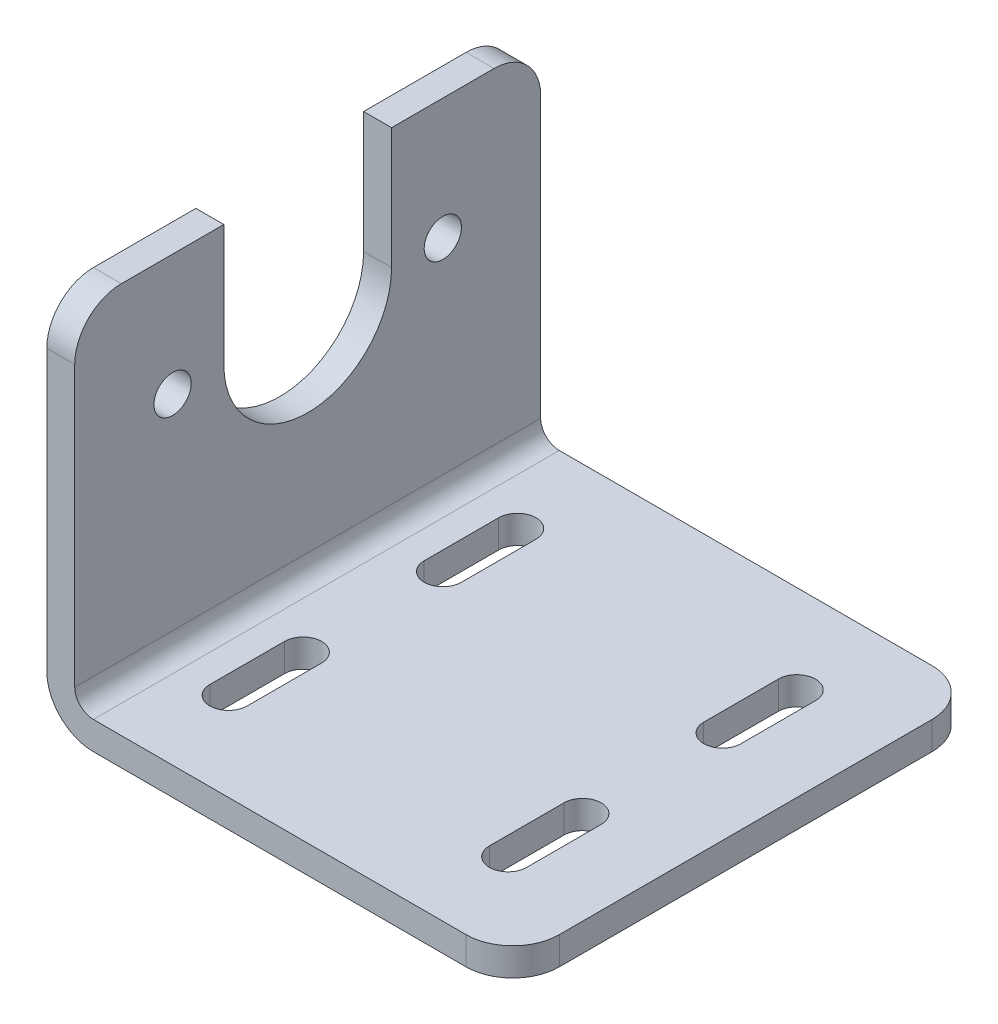
SolidWorks part; units mm, degrees
ref_plane "前视基准面" through (0, 0, 0) normal (0, 0, 1) x (1, 0, 0)
ref_plane "上视基准面" through (0, 0, 0) normal (0, 1, 0) x (1, 0, 0)
ref_plane "右视基准面" through (0, 0, 0) normal (1, 0, 0) x (0, 0, -1)
sketch "草图1" plane through (0, 0, 0) normal (0, 0, 1) x (1, 0, 0)
  line L0 (0, 19.7922) -> (0, -15.2078)
  line L1 (2, -17.2078) -> (47, -17.2078)
  line L2 (47, -17.2078) -> (47, -20.2078)
  line L3 (47, -20.2078) -> (-3, -20.2078)
  line L4 (-3, -20.2078) -> (-3, 19.7922)
  line L5 (-3, 19.7922) -> (0, 19.7922)
  arc A0 (2, -17.2078) -> (0, -15.2078) centre (2, -15.2078) cw
  dimension "D5" = 2
  dimension "D1" = 50
  dimension "D2" = 3
  dimension "D3" = 40
  dimension "D4" = 3
extrude "凸台-拉伸1" add sketch "草图1" along normal blind 50
sketch "草图2" plane through (-3, 0, 0) normal (-1, 0, 0) x (0, 0, 1)
  line L0 (50, 19.7922) -> (34, 19.7922)
  line L1 (50, 19.7922) -> (0, 19.7922) construction
  line L2 (0, 19.7922) -> (16, 19.7922)
  line L3 (16, 19.7922) -> (16, 6.7922)
  line L4 (34, 19.7922) -> (34, 6.7922)
  line L5 (16, 19.7922) -> (34, 19.7922)
  arc A0 (34, 6.7922) -> (16, 6.7922) centre (25, 6.7922) cw
  circle A1 centre (39.5, 6.7922) radius 2
  circle A2 centre (10.5, 6.7922) radius 2
  line M13 (50, 19.7922) -> (0, 19.7922)
  dimension "D1" = 16
  dimension "D2" = 16
  dimension "D3" = 13
  dimension "D4" = 13
extrude "切除-拉伸1" cut sketch "草图2" against normal blind 3 contours A2 | A0 L4 L3 M13 | A1
sketch "草图3" plane through (0, -20.2078, 0) normal (0, -1, 0) x (1, 0, 0)
  line L0 (39, 32.5) -> (39, 40.5)
  line L1 (47, 50) -> (47, 0) construction
  line L3 (35, 32.5) -> (35, 40.5)
  line L4 (-3, 25) -> (47, 25) construction
  line L5 (-3, 50) -> (-3, 0) construction
  line L7 (35, 17.5) -> (35, 9.5)
  line L8 (39, 17.5) -> (39, 9.5)
  line L9 (5, 17.5) -> (5, 9.5)
  line L10 (9, 17.5) -> (9, 9.5)
  line L11 (9, 32.5) -> (9, 40.5)
  line L12 (5, 32.5) -> (5, 40.5)
  arc A0 (35, 9.5) -> (39, 9.5) centre (37, 9.5) ccw
  arc A1 (39, 17.5) -> (35, 17.5) centre (37, 17.5) ccw
  arc A2 (9, 9.5) -> (5, 9.5) centre (7, 9.5) cw
  arc A3 (5, 17.5) -> (9, 17.5) centre (7, 17.5) cw
  arc A4 (39, 32.5) -> (35, 32.5) centre (37, 32.5) cw
  arc A5 (35, 40.5) -> (39, 40.5) centre (37, 40.5) cw
  arc A6 (5, 32.5) -> (9, 32.5) centre (7, 32.5) ccw
  arc A7 (9, 40.5) -> (5, 40.5) centre (7, 40.5) ccw
  dimension "D2" = 4
  dimension "D1" = 2
extrude "切除-拉伸2" cut sketch "草图3" against normal blind 3
fillet "圆角1" radius 5 1 edges at (-3, -20.2078, 25)
fillet "圆角2" radius 5 4 edges at (47, -18.7078, 0) (47, -18.7078, 50) (-1.5, 19.7922, 0) (-1.5, 19.7922, 50)
